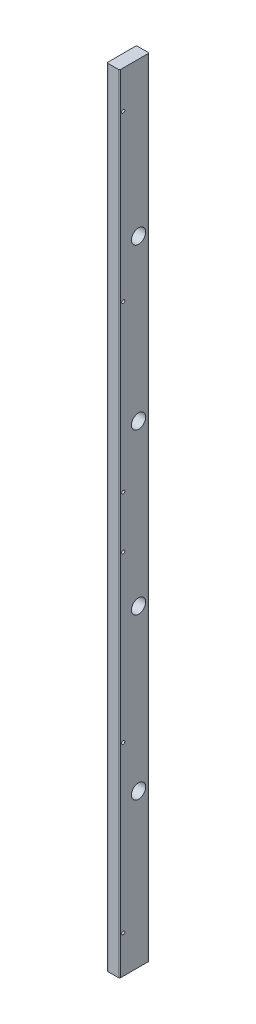
SolidWorks part; units mm, degrees
ref_plane "Front" through (0, 0, 0) normal (0, 0, 1) x (1, 0, 0)
ref_plane "Top" through (0, 0, 0) normal (0, 1, 0) x (1, 0, 0)
ref_plane "Right" through (0, 0, 0) normal (1, 0, 0) x (0, 0, -1)
sketch "Sketch1" plane through (0, 0, 0) normal (0, 1, 0) x (1, 0, 0)
  line L1 (-19.05, -44.45) -> (19.05, -44.45)
  line L2 (-19.05, -44.45) -> (-19.05, 44.45)
  line L3 (-19.05, 44.45) -> (19.05, 44.45)
  line L4 (19.05, -44.45) -> (19.05, 44.45)
  line L5 (-19.05, -44.45) -> (19.05, 44.45) construction
  line L6 (-19.05, 44.45) -> (19.05, -44.45) construction
  point P0 (0, 0)
  dimension "D1" = 38.1
  dimension "D2" = 88.9
extrude "Boss-Extrude1" add sketch "Sketch1" along normal blind 2362.2
sketch "Sketch2" plane through (19.05, 0, 0) normal (1, 0, 0) x (0, 0, -1)
  line L0 (-44.45, 0) -> (44.45, 0) construction
  line L1 (44.45, 2362.2) -> (44.45, 0) construction
  circle A0 centre (12.7, 458.7875) radius 21.4313
  circle A1 centre (12.7, 939.8) radius 21.4313
  circle A2 centre (12.7, 1420.8443) radius 21.4312
  circle A3 centre (12.7, 1901.8885) radius 21.4313
  dimension "D1" = 42.8625
  dimension "D2" = 31.75
  dimension "D3" = 458.7875
  dimension "D4" = 481.0125
  dimension "D6" = 481.0443
  dimension "D5" = 3
extrude "Cut-Extrude4" cut sketch "Sketch2" against normal blind 918.6545
ref_plane "Plane1" through (0, 1181.1, 0) normal (0, 1, 0) x (1, 0, 0)
sketch "Sketch3" plane through (19.05, 0, 0) normal (1, 0, 0) x (0, 0, -1)
  line L0 (-44.45, 2362.2) -> (-44.45, 0) construction
  line L2 (-44.45, 0) -> (44.45, 0) construction
  circle A0 centre (-33.3375, 112.7125) radius 4.7625
  circle A1 centre (-33.3375, 608.0125) radius 4.7625
  circle A2 centre (-33.3375, 1103.3125) radius 4.7625
  dimension "D1" = 9.525
  dimension "D2" = 11.1125
  dimension "D3" = 112.7125
  dimension "D4" = 608.0125
  dimension "D5" = 1103.3125
extrude "Cut-Extrude5" cut sketch "Sketch3" against normal through all
fillet "Fillet1" radius 3.175 4 edges at (-19.05, 1181.1, -44.45) (-19.05, 1181.1, 44.45) (19.05, 1181.1, -44.45) (19.05, 1181.1, 44.45)
mirror "Mirror1" about plane through (0, 1181.1, 0) normal (0, 1, 0) of "Cut-Extrude5"
